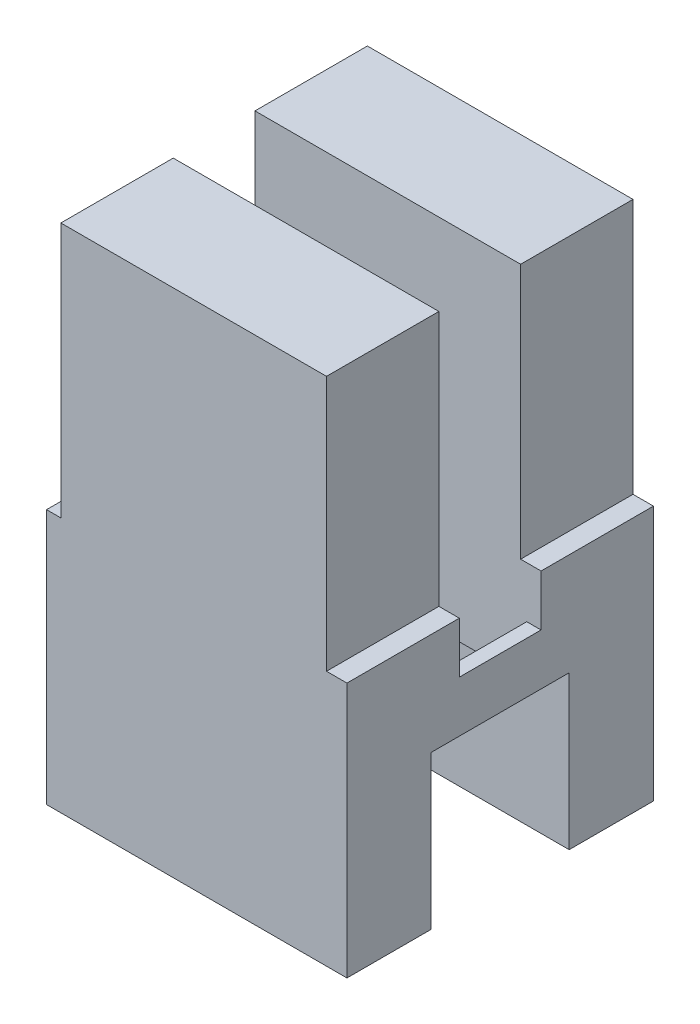
SolidWorks part; units mm, degrees
ref_plane "Front Plane" through (0, 0, 0) normal (0, 0, 1) x (1, 0, 0)
ref_plane "Top Plane" through (0, 0, 0) normal (0, 1, 0) x (1, 0, 0)
ref_plane "Right Plane" through (0, 0, 0) normal (1, 0, 0) x (0, 0, -1)
sketch "Sketch1" plane through (0, 0, 0) normal (0, 1, 0) x (1, 0, 0)
  line L1 (-18.669, 19.05) -> (18.669, 19.05)
  line L2 (-18.669, 19.05) -> (-18.669, -19.05)
  line L3 (-18.669, -19.05) -> (18.669, -19.05)
  line L4 (18.669, 19.05) -> (18.669, -19.05)
  line L5 (-18.669, 19.05) -> (18.669, -19.05) construction
  line L6 (-18.669, -19.05) -> (18.669, 19.05) construction
  point P0 (0, 0)
  dimension "D1" = 38.1
  dimension "D2" = 37.338
extrude "Boss-Extrude1" add sketch "Sketch1" along normal blind 63.5
sketch "Sketch3" plane through (0, 63.5, 0) normal (0, 1, 0) x (1, 0, 0)
  line L0 (18.669, -19.05) -> (18.669, 19.05) construction
  line L1 (-18.669, 5.08) -> (18.669, 5.08)
  line L2 (-18.669, 5.08) -> (-18.669, -5.08)
  line L3 (-18.669, -5.08) -> (18.669, -5.08)
  line L4 (18.669, 5.08) -> (18.669, -5.08)
  line L5 (-18.669, 5.08) -> (18.669, -5.08) construction
  line L6 (-18.669, -5.08) -> (18.669, 5.08) construction
  point P0 (0, 0)
  dimension "D1" = 10.16
extrude "Cut-Extrude1" cut sketch "Sketch3" against normal blind 38.1
sketch "Sketch4" plane through (0, 0, 0) normal (0, -1, 0) x (1, 0, 0)
  line L0 (18.669, 19.05) -> (18.669, -19.05) construction
  line L1 (-18.669, -8.5725) -> (18.669, -8.5725)
  line L2 (-18.669, -8.5725) -> (-18.669, 8.5725)
  line L3 (-18.669, 8.5725) -> (18.669, 8.5725)
  line L4 (18.669, -8.5725) -> (18.669, 8.5725)
  line L5 (-18.669, -8.5725) -> (18.669, 8.5725) construction
  line L6 (-18.669, 8.5725) -> (18.669, -8.5725) construction
  point P0 (0, 0)
  dimension "D1" = 17.145
extrude "Cut-Extrude2" cut sketch "Sketch4" against normal offset from surface (19.05 mm away) 6.35 up to face at (0, 25.4, 0)
sketch "Sketch5" plane through (0, 25.4, 0) normal (0, 1, 0) x (1, 0, 0)
  line L0 (18.669, 5.08) -> (-18.669, 5.08) construction
  line L1 (-16.891, -5.08) -> (16.891, -5.08)
  line L2 (-16.891, -5.08) -> (-16.891, 5.08)
  line L3 (-16.891, 5.08) -> (16.891, 5.08)
  line L4 (16.891, -5.08) -> (16.891, 5.08)
  line L5 (-16.891, -5.08) -> (16.891, 5.08) construction
  line L6 (-16.891, 5.08) -> (16.891, -5.08) construction
  line L7 (-16.891, 5.08) -> (-18.669, 5.08) construction
  line L8 (16.891, 5.08) -> (18.669, 5.08) construction
  point P0 (0, 0)
  dimension "D1" = 1.778
extrude "Cut-Extrude3" cut sketch "Sketch5" against normal through all
sketch "Sketch6" plane through (0, 63.5, 0) normal (0, 1, 0) x (1, 0, 0)
  line L0 (-18.669, -19.05) -> (18.669, -19.05) construction
  line L1 (18.669, 19.05) -> (16.129, 19.05)
  line L2 (18.669, 19.05) -> (18.669, -19.05)
  line L3 (18.669, -19.05) -> (16.129, -19.05)
  line L4 (16.129, 19.05) -> (16.129, -19.05)
  line L6 (-18.669, 19.05) -> (-16.891, 19.05)
  line L7 (-18.669, 19.05) -> (-18.669, -19.05)
  line L8 (-18.669, -19.05) -> (-16.891, -19.05)
  line L9 (-16.891, 19.05) -> (-16.891, -19.05)
  dimension "D1" = 2.54
  dimension "D2" = 1.778
extrude "Cut-Extrude4" cut sketch "Sketch6" against normal offset from surface (31.75 mm away) 6.35 up to face at (-17.78, 25.4, 0)
